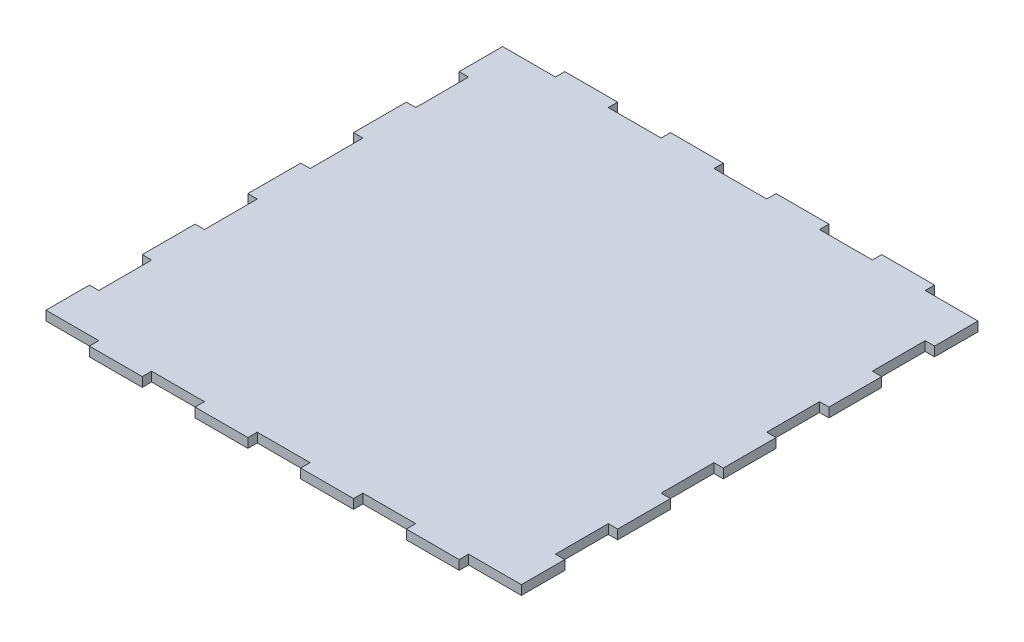
SolidWorks part; units mm, degrees
ref_plane "Front Plane" through (0, 0, 0) normal (0, 0, 1) x (1, 0, 0)
ref_plane "Top Plane" through (0, 0, 0) normal (0, 1, 0) x (1, 0, 0)
ref_plane "Right Plane" through (0, 0, 0) normal (1, 0, 0) x (0, 0, -1)
sketch "Sketch1" plane through (0, 0, 0) normal (0, 1, 0) x (1, 0, 0)
  line L0 (-76, -73) -> (-59.1111, -73)
  line L1 (-76, -76) -> (76, -76) construction
  line L2 (-76, -76) -> (-76, 76) construction
  line L3 (-76, 76) -> (76, 76) construction
  line L4 (76, -76) -> (76, 76) construction
  line L5 (0, 76) -> (0, -76) construction
  line L6 (-76, 0) -> (76, 0) construction
  line L7 (-59.1111, -73) -> (-59.1111, -76)
  line L8 (-59.1111, -76) -> (-42.2222, -76)
  line L9 (-42.2222, -76) -> (-42.2222, -73)
  line L10 (-42.2222, -73) -> (-25.3333, -73)
  line L11 (-25.3333, -73) -> (-25.3333, -76)
  line L12 (-25.3333, -76) -> (-8.4444, -76)
  line L13 (-8.4444, -76) -> (-8.4444, -73)
  line L14 (-8.4444, -73) -> (0, -73)
  line L15 (0, -73) -> (0, 0)
  line L16 (0, 0) -> (-76, 0)
  line L17 (-76, 0) -> (-76, -8.4444)
  line L18 (-76, -8.4444) -> (-73, -8.4444)
  line L19 (-73, -8.4444) -> (-73, -25.3333)
  line L20 (-73, -25.3333) -> (-76, -25.3333)
  line L21 (-76, -25.3333) -> (-76, -42.2222)
  line L22 (-76, -42.2222) -> (-73, -42.2222)
  line L23 (-73, -42.2222) -> (-73, -59.1111)
  line L24 (-73, -59.1111) -> (-76, -59.1111)
  line L25 (-76, -59.1111) -> (-76, -73)
  point P140 (0, 0)
  dimension "D1" = 152
  dimension "D2" = 3
  dimension "D3" = 3
  dimension "D4" = 16.8889
  dimension "D5" = 13.8889
extrude "Boss-Extrude1" add sketch "Sketch1" along normal blind 3
mirror "Mirror1" about plane through (0, 0, 0) normal (1, 0, 0) of "Boss-Extrude1"
